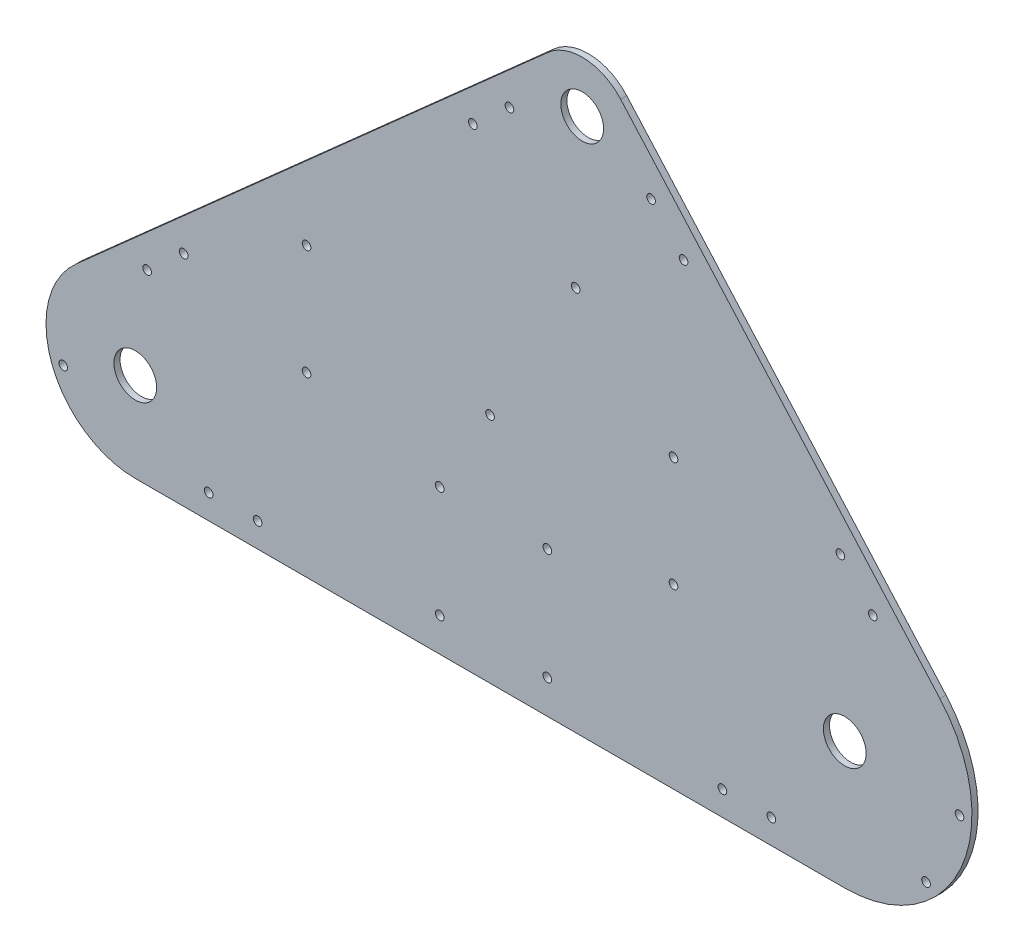
SolidWorks part; units mm, degrees
ref_plane "Front Plane" through (0, 0, 0) normal (0, 0, 1) x (1, 0, 0)
ref_plane "Top Plane" through (0, 0, 0) normal (0, 1, 0) x (1, 0, 0)
ref_plane "Right Plane" through (0, 0, 0) normal (1, 0, 0) x (0, 0, -1)
sketch "Sketch1" plane through (0, 0, 0) normal (0, 0, 1) x (1, 0, 0)
  line L4 (-188.2646, 81.0118) -> (56.8098, 298.7045)
  line L5 (-157.48, 0) -> (210.82, 0)
  line L9 (94.461, 296.4767) -> (260.194, 109.8976)
  line L10 (-157.48, 46.355) -> (18.5166, 46.355) construction
  line L11 (15.767, 41.5925) -> (21.2662, 41.5925) construction
  line L12 (21.2662, 41.5925) -> (24.0159, 46.355) construction
  line L13 (24.0159, 46.355) -> (21.2662, 51.1175) construction
  line L14 (21.2662, 51.1175) -> (15.767, 51.1175) construction
  line L15 (15.767, 51.1175) -> (13.0173, 46.355) construction
  line L16 (13.0173, 46.355) -> (15.767, 41.5925) construction
  line L19 (0.5561, 64.3155) -> (36.4771, 64.3155) construction
  line L20 (0.5561, 64.3155) -> (0.5561, 28.3945) construction
  line L21 (0.5561, 28.3945) -> (36.4771, 28.3945) construction
  line L22 (36.4771, 64.3155) -> (36.4771, 28.3945) construction
  line L23 (0.5561, 64.3155) -> (36.4771, 28.3945) construction
  line L24 (0.5561, 28.3945) -> (36.4771, 64.3155) construction
  arc A3 (-188.2646, 81.0118) -> (-157.48, 0) centre (-157.48, 46.355) ccw
  arc A4 (210.82, 0) -> (260.194, 109.8976) centre (210.82, 66.04) ccw
  arc A5 (94.461, 296.4767) -> (56.8098, 298.7045) centre (74.5215, 278.765) ccw
  circle A7 centre (-157.48, 46.355) radius 11.0998
  circle A8 centre (74.5215, 278.765) radius 11.0998
  circle A9 centre (210.82, 66.04) radius 11.0998
  circle A10 centre (18.5166, 46.355) radius 4.7625 construction
  circle A11 centre (18.5166, 46.355) radius 9.525
  dimension "D3" = 19.685
  dimension "D4" = 90
  dimension "D5" = 232.41
  dimension "D2" = 368.3
  dimension "D6" = 92.71
  dimension "D7" = 53.34
  dimension "D8" = 132.08
  dimension "D10" = 22.1996
  dimension "D11" = 9.525
  dimension "D14" = 50.8
  dimension "D12" = 19.05
  dimension "D13" = 175.9966
extrude "Boss-Extrude1" add sketch "Sketch1" along normal blind 3.175 contours L9 A4 L5 A3 L4 A5 | A7 | A8 | A9
sketch "Sketch6" plane through (0, 0, 3.175) normal (0, 0, 1) x (1, 0, 0)
  line L1 (0.5563, 75.2475) -> (56.4363, 75.2475)
  line L2 (0.5563, 75.2475) -> (0.5563, 17.4625)
  line L3 (-157.48, 46.355) -> (-188.2646, 81.0118) construction
  line L4 (-157.48, 46.355) -> (-157.48, 0) construction
  line L5 (210.82, 66.04) -> (210.82, 0) construction
  line L6 (210.82, 66.04) -> (260.194, 109.8976) construction
  line L7 (74.5215, 278.765) -> (56.8098, 298.7045) construction
  line L8 (94.461, 296.4767) -> (260.194, 109.8976) construction
  line L9 (-188.2646, 81.0118) -> (56.8098, 298.7045) construction
  line L10 (74.5215, 278.765) -> (94.461, 296.4767) construction
  line L11 (26.67, 271.9322) -> (26.67, 0) construction
  line L12 (-188.2646, 81.0118) -> (56.8098, 298.7045) construction
  line L13 (-157.48, 0) -> (210.82, 0) construction
  line L14 (210.82, 66.04) -> (276.7447, 62.1393) construction
  line L15 (121.92, 92.075) -> (-68.58, 92.075) construction
  line L16 (121.92, 92.075) -> (121.92, 149.225) construction
  line L17 (121.92, 149.225) -> (-68.58, 149.225) construction
  line L18 (-68.58, 92.075) -> (-68.58, 149.225) construction
  line L19 (121.92, 92.075) -> (-68.58, 149.225) construction
  line L20 (121.92, 149.225) -> (-68.58, 92.075) construction
  line L21 (210.82, 66.04) -> (257.5173, 19.3427) construction
  line L22 (-157.48, 46.355) -> (-200.8119, 29.8888) construction
  line L23 (-157.48, 0) -> (210.82, 0) construction
  line L24 (94.461, 296.4767) -> (260.194, 109.8976) construction
  line L25 (0.5563, 17.4625) -> (56.4363, 17.4625)
  line L26 (56.4363, 75.2475) -> (56.4363, 17.4625)
  arc A0 (210.82, 0) -> (260.194, 109.8976) centre (210.82, 66.04) ccw construction
  arc A1 (-188.2646, 81.0118) -> (-157.48, 0) centre (-157.48, 46.355) ccw construction
  arc A2 (210.82, 0) -> (260.194, 109.8976) centre (210.82, 66.04) ccw construction
  arc A3 (94.461, 296.4767) -> (56.8098, 298.7045) centre (74.5215, 278.765) ccw construction
  arc A4 (-188.2646, 81.0118) -> (-157.48, 0) centre (-157.48, 46.355) ccw construction
  point P0 (-119.38, 12.7)
  point P1 (-93.98, 12.7)
  point P2 (147.32, 12.7)
  point P3 (172.72, 12.7)
  point P4 (-151.3455, 96.8192)
  point P5 (-132.3555, 113.6875)
  point P6 (17.7689, 247.0388)
  point P7 (36.7589, 263.9071)
  point P8 (110.2685, 259.5575)
  point P9 (127.1368, 240.5675)
  point P12 (208.5283, 148.9385)
  point P13 (225.3966, 129.9484)
  point P44 (26.67, 120.65)
  point P50 (71.12, 200.025)
  point P60 (-194.876, 32.1444)
  point P61 (270.3947, 62.515)
  point P62 (253.0272, 23.8328)
  dimension "D28" = 6.35
  dimension "D4" = 12.7
  dimension "D5" = 12.7
  dimension "D6" = 25.4
  dimension "D7" = 38.1
  dimension "D8" = 38.1
  dimension "D9" = 25.4
  dimension "D10" = 25.4
  dimension "D11" = 12.7
  dimension "D12" = 12.7
  dimension "D13" = 25.4
  dimension "D14" = 38.1
  dimension "D15" = 12.7
  dimension "D16" = 12.7
  dimension "D17" = 38.1
  dimension "D18" = 25.4
  dimension "D19" = 25.4
  dimension "D20" = 38.1
  dimension "D21" = 38.1
  dimension "D22" = 184.15
  dimension "D23" = 57.15
  dimension "D24" = 190.5
  dimension "D25" = 120.65
  dimension "D26" = 45
  dimension "D27" = 45
  dimension "D29" = 6.35
  dimension "D30" = 6.35
  dimension "D31" = 50.8
  dimension "D32" = 50.8
  dimension "D33" = 12.7
  dimension "D34" = 12.7
  dimension "D35" = 12.7
  dimension "D36" = 57.785
  dimension "D37" = 55.88
  dimension "D38" = 158.0363
  dimension "D39" = 17.4625
hole_wizard "#8 Clearance Hole2" positions "Sketch7" profile "Sketch8" hole size "#8" standard "ANSI Inch" end condition through all
sketch "Sketch7" plane through (0, 0, 3.175) normal (0, 0, 1) x (1, 0, 0)
  point P0 (17.7689, 247.0388)
  point P3 (36.7589, 263.9071)
  point P6 (110.2685, 259.5575)
  point P9 (127.1368, 240.5675)
  point P12 (208.5283, 148.9385)
  point P15 (225.3966, 129.9484)
  point P18 (270.3947, 62.515)
  point P21 (253.0272, 23.8328)
  point P24 (172.72, 12.7)
  point P27 (147.32, 12.7)
  point P30 (-93.98, 12.7)
  point P33 (-119.38, 12.7)
  point P36 (-194.876, 32.1444)
  point P39 (-151.3455, 96.8192)
  point P42 (-132.3555, 113.6875)
  point P45 (-68.58, 149.225)
  point P48 (-68.58, 92.075)
  point P51 (121.92, 92.075)
  point P54 (121.92, 149.225)
  point P57 (71.12, 200.025)
  point P61 (26.67, 120.65)
  point P64 (0.5563, 75.2475)
  point P67 (56.4363, 75.2475)
  point P70 (56.4363, 17.4625)
  point P73 (0.5563, 17.4625)
sketch "Sketch8" plane through (17.7689, 247.0388, 3.175) normal (1, 0, 0) x (0, -1, 0)
  line L0 (0, 0) -> (0, 3.175)
  line L1 (0, 3.175) -> (2.2479, 3.175)
  line L2 (2.2479, 3.175) -> (2.2479, 0)
  line L5 (2.2479, 0) -> (0, 0)
  line L11 (0, -6.35) -> (0, 107.95) construction
  dimension "Thru Hole Dia." = 4.4958
  dimension "Thru Hole Depth" = 3.175
